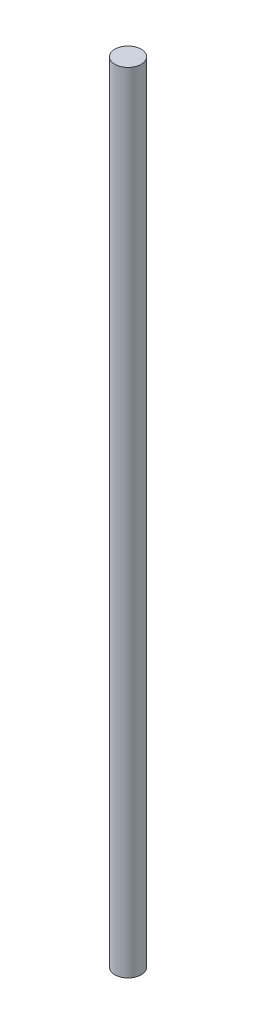
SolidWorks part; units mm, degrees
ref_plane "前视基准面" through (0, 0, 0) normal (0, 0, 1) x (1, 0, 0)
ref_plane "上视基准面" through (0, 0, 0) normal (0, 1, 0) x (1, 0, 0)
ref_plane "右视基准面" through (0, 0, 0) normal (1, 0, 0) x (0, 0, -1)
other "Configuration Table"
sketch "草图1" plane through (0, 0, 0) normal (0, 1, 0) x (1, 0, 0)
  circle A0 centre (0, 0) radius 1.5
  dimension "D1" = 3
extrude "凸台-拉伸1" add sketch "草图1" along normal blind 90
